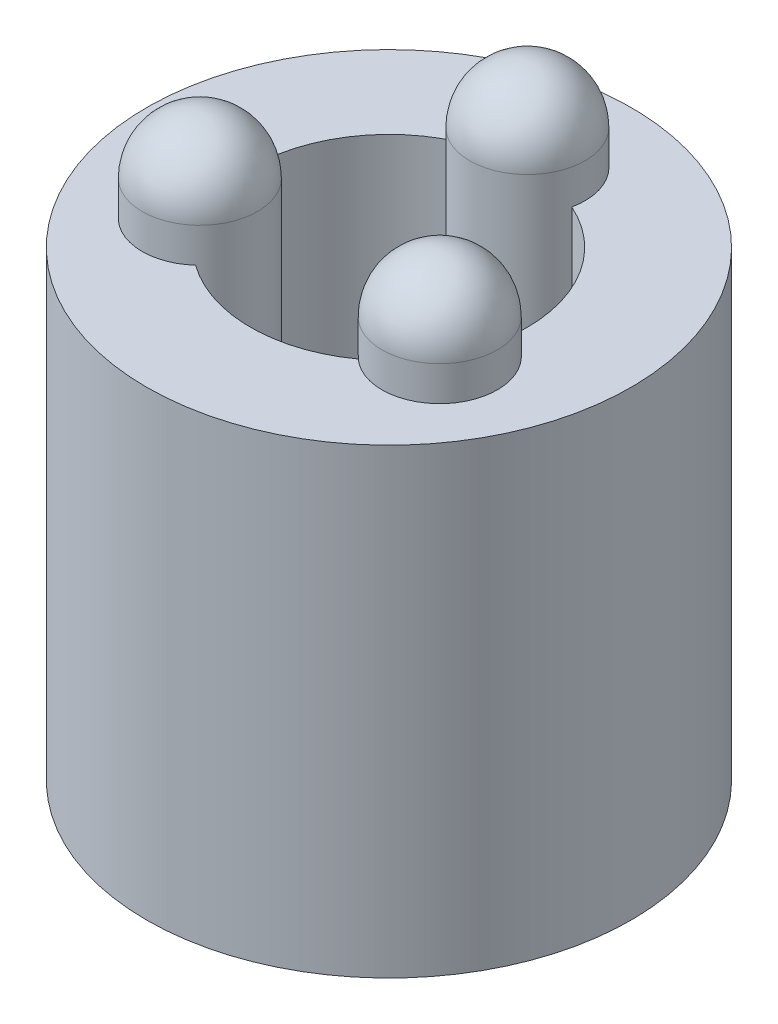
SolidWorks part; units mm, degrees
ref_plane "Alzado" through (0, 0, 0) normal (0, 0, 1) x (1, 0, 0)
ref_plane "Planta" through (0, 0, 0) normal (0, 1, 0) x (1, 0, 0)
ref_plane "Vista lateral" through (0, 0, 0) normal (1, 0, 0) x (0, 0, -1)
sketch "Croquis1" plane through (0, 0, 0) normal (0, 1, 0) x (1, 0, 0)
  circle A0 centre (0, 0) radius 5.25
  dimension "D1" = 10.5
extrude "Saliente-Extruir1" add sketch "Croquis1" along normal blind 10
sketch "Croquis2" plane through (0, 10, 0) normal (0, 1, 0) x (1, 0, 0)
  circle A0 centre (0, 0) radius 3
  dimension "D1" = 6
extrude "Cortar-Extruir1" cut sketch "Croquis2" against normal blind 10
sketch "Croquis3" plane through (0, 10, 0) normal (0, 1, 0) x (1, 0, 0)
  circle A0 centre (0, 0) radius 3 construction
  circle A1 centre (0, 3) radius 1.25
  circle A2 centre (0.0015, 0.0009) radius 3 construction
  circle A3 centre (2.5996, -1.4991) radius 1.25
  circle A4 centre (0.0015, -0.0009) radius 3 construction
  circle A5 centre (-2.5966, -1.5009) radius 1.25
  point P15 (0.001, 0)
  dimension "D1" = 6
  dimension "D2" = 2.5
extrude "Saliente-Extruir2" add sketch "Croquis3" along normal blind 2 and the other way through all
fillet "Redondeo1" radius 1.25 3 edges at (0, 12, -1.75) (2.5996, 12, 2.7491) (-2.5966, 12, 2.7509)
